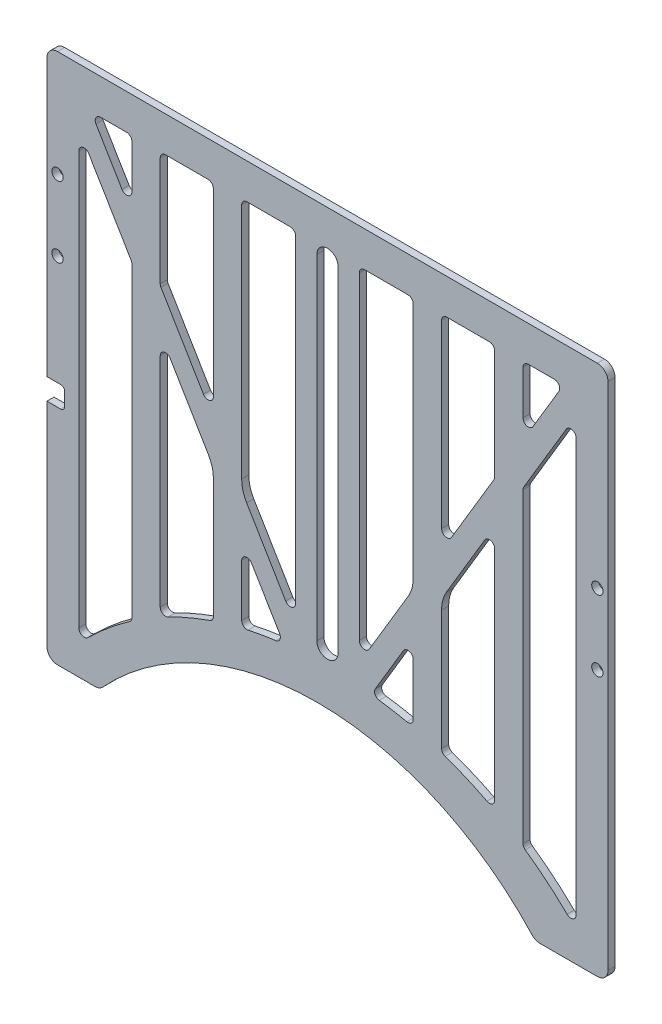
SolidWorks part; units mm, degrees
material "Thornel Mat VMA"
ref_plane "前视基准面" through (0, 0, 0) normal (0, 0, 1) x (1, 0, 0)
ref_plane "上视基准面" through (0, 0, 0) normal (0, 1, 0) x (1, 0, 0)
ref_plane "右视基准面" through (0, 0, 0) normal (1, 0, 0) x (0, 0, -1)
sketch "草图1" plane through (0, 0, 0) normal (0, 0, 1) x (1, 0, 0)
  line L1 (-79.225, -75) -> (79.225, -75)
  line L2 (-79.225, -75) -> (-79.225, 75)
  line L3 (-79.225, 75) -> (79.225, 75)
  line L4 (79.225, -75) -> (79.225, 75)
  line L5 (-79.225, -75) -> (79.225, 75) construction
  line L6 (-79.225, 75) -> (79.225, -75) construction
  point P0 (0, 0)
  dimension "D1" = 158.45
  dimension "D2" = 150
extrude "凸台-拉伸1" add sketch "草图1" along normal blind 2
sketch "草图2" plane through (0, 0, 0) normal (0, 0, -1) x (-1, 0, 0)
  line L0 (2.825, 0) -> (2.825, -130) construction
  line L1 (-79.225, -75) -> (-79.225, 75) construction
  circle A0 centre (2.825, -130) radius 82.5
  dimension "D1" = 165
  dimension "D2" = 130
  dimension "D3" = 82.05
  dimension "D4" = 130
extrude "切除-拉伸1" cut sketch "草图2" against normal blind 10
sketch "草图4" plane through (0, 0, 0) normal (0, 0, -1) x (-1, 0, 0)
  line L2 (79.225, 75) -> (79.225, -75) construction
  line L3 (74.225, -12) -> (84.225, -12)
  line L4 (74.225, -12) -> (74.225, -6)
  line L5 (74.225, -6) -> (84.225, -6)
  line L6 (84.225, -12) -> (84.225, -6)
  line L7 (74.225, -12) -> (84.225, -6) construction
  line L8 (74.225, -6) -> (84.225, -12) construction
  point P2 (79.225, -9)
  dimension "D1" = 5
  dimension "D2" = 6
  dimension "D3" = 9
extrude "切除-拉伸2" cut sketch "草图4" against normal blind 10
fillet "圆角1" radius 1.1 2 edges at (-74.225, -12, 1) (-74.225, -6, 1)
sketch "草图5" plane through (0, 0, 2) normal (0, 0, 1) x (1, 0, 0)
  line L0 (0, 0) -> (-76.225, 0) construction
  line L1 (-76.225, 0) -> (-76.225, 25) construction
  line L2 (-76.225, 25) -> (-76.225, 45) construction
  line L3 (0, 0) -> (76.225, 0) construction
  line L4 (76.225, 0) -> (76.225, 20) construction
  line L5 (-79.225, 75) -> (-79.225, -6) construction
  line L6 (79.225, -75) -> (79.225, 75) construction
  circle A4 centre (76.225, 20) radius 1.6
  circle A5 centre (76.225, 0) radius 1.6
  circle A6 centre (-76.225, 45) radius 1.6
  circle A7 centre (-76.225, 25) radius 1.6
  dimension "D6" = 3.2
  dimension "D1" = 3
  dimension "D2" = 20
  dimension "D3" = 3
  dimension "D4" = 25
  dimension "D5" = 20
extrude "切除-拉伸3" cut sketch "草图5" against normal blind 10
sketch "草图6" plane through (0, 0, 2) normal (0, 0, 1) x (1, 0, 0)
  line L0 (-70.225, 65) -> (-70.225, -66.6479)
  line L1 (-9, 65) -> (-9, -37.5431) construction
  line L2 (-70.225, 65) -> (70.225, 65)
  line L3 (70.225, 65) -> (70.225, -73.2554)
  line L4 (79.225, 75) -> (-79.225, 75) construction
  line L5 (-55.225, 65) -> (-55.225, -53.7734)
  line L6 (0, 65) -> (0, -37.5431) construction
  line L7 (-9, 65) -> (-9, -38.6562)
  line L8 (4, 65) -> (4, -37.5431)
  line L9 (-47.225, 65) -> (-47.225, -48.8527)
  line L10 (-32.225, 65) -> (-32.225, -42.2966)
  line L11 (-24.225, 65) -> (-24.225, -40.0095)
  circle A1 centre (76.225, 0) radius 1.6 construction
  arc A2 (66.1204, -68.3333) -> (-71.7704, -68.3333) centre (-2.825, -130) ccw
  arc A3 (70.225, -73.2554) -> (-70.225, -66.6479) centre (-2.825, -130) ccw
  circle A4 centre (-76.225, 25) radius 1.6 construction
  dimension "D2" = 6
  dimension "D3" = 6
  dimension "D4" = 10
  dimension "D5" = 15
  dimension "D8" = 8
  dimension "D9" = 15
  dimension "D10" = 8
  dimension "D1" = 10
  dimension "D6" = 9
  dimension "D7" = 4
extrude "切除-拉伸4" cut sketch "草图6" against normal blind 10 contours A3 L5 L2 L0 | A3 L10 L2 L9 | A3 L7 L2 L11
mirror "镜向1" about plane through (0, 0, 0) normal (1, 0, 0) of "切除-拉伸4"
sketch "草图7" plane through (0, 0, 2) normal (0, 0, 1) x (1, 0, 0)
  line L0 (-70.225, 65) -> (-9, -37.7063) construction
  line L1 (70.225, 65) -> (9, -37.7063) construction
  line L2 (-72.8019, 63.4639) -> (-11.5769, -39.2425)
  line L3 (-67.6481, 66.5361) -> (-6.4231, -36.1702)
  line L4 (67.6481, 66.5361) -> (6.4231, -36.1702)
  line L5 (72.8019, 63.4639) -> (11.5769, -39.2425)
  line L6 (67.6481, 66.5361) -> (72.8019, 63.4639)
  line L7 (6.4231, -36.1702) -> (11.5769, -39.2425)
  line L8 (-6.4231, -36.1702) -> (-11.5769, -39.2425)
  line L9 (-67.6481, 66.5361) -> (-72.8019, 63.4639)
  dimension "D1" = 3
  dimension "D2" = 3
  dimension "D3" = 3
  dimension "D4" = 3
extrude "凸台-拉伸2" add sketch "草图7" against normal up to surface (2 mm away) up to face at (62.8112, 2.4951, 0)
fillet "圆角2" radius 1.5 40 edges at (-9, -31.8474, 1) (-9, 65, 1) (-24.225, 65, 1) (-32.225, 7.113, 1) (-32.225, 65, 1) (-47.225, 65, 1) (-47.225, 32.2759, 1) (-55.225, 65, 1) (-70.225, 59.1411, 1) (-70.225, -66.6479, 1) (-55.225, -53.7734, 1) (-55.225, 33.9783, 1) (-47.225, 20.5581, 1) (-47.225, -48.8527, 1) (-32.225, -42.2966, 1) (-24.225, -18.025, 1) (-24.225, -40.0095, 1) (-12.3241, -37.989, 1) (12.3241, -37.989, 1) (24.225, -40.0095, 1) (24.225, -18.025, 1) (32.225, -42.2966, 1) (47.225, -48.8527, 1) (47.225, 20.5581, 1) (55.225, 33.9783, 1) (55.225, -53.7734, 1) (70.225, -66.6479, 1) (70.225, 59.1411, 1) (66.7324, 65, 1) (55.225, 65, 1) (55.225, 45.6961, 1) (47.225, 32.2759, 1) (47.225, 65, 1) (32.225, 65, 1) (32.225, 7.113, 1) (24.225, 65, 1) (9, 65, 1) (9, -31.8474, 1) (-55.225, 45.6961, 1) (-66.7324, 65, 1)
fillet "圆角3" radius 10 4 edges at (-24.225, -6.3072, 1) (-32.225, -4.6048, 1) (24.225, -6.3072, 1) (32.225, -4.6048, 1)
fillet "圆角4" radius 3 6 edges at (-64.3169, -75, 1) (58.6669, -75, 1) (79.225, -75, 1) (79.225, 75, 1) (-79.225, 75, 1) (-79.225, -75, 1)
sketch "草图10" plane through (0, 0, 2) normal (0, 0, 1) x (1, 0, 0)
  line L0 (0, 62) -> (0, -32.5) construction
  line L1 (3, 62) -> (3, -32.5)
  line L2 (-3, 62) -> (-3, -32.5)
  line L3 (22.725, 65) -> (10.5, 65) construction
  arc A0 (3, 62) -> (-3, 62) centre (0, 62) ccw
  arc A1 (-3, -32.5) -> (3, -32.5) centre (0, -32.5) ccw
  arc A2 (57.79, -74.0351) -> (-63.44, -74.0351) centre (-2.825, -130) ccw construction
  point P3 (0, 14.75)
  dimension "D2" = 3
  dimension "D1" = 15
extrude "切除-拉伸5" cut sketch "草图10" against normal blind 10
